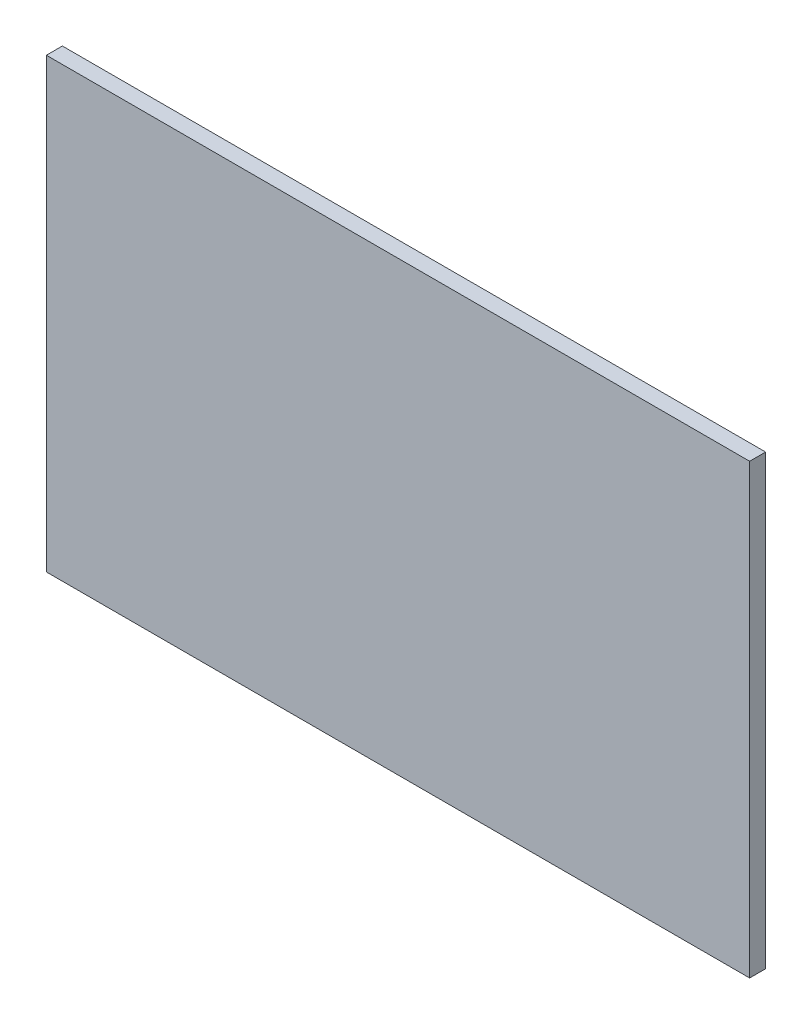
SolidWorks part; units mm, degrees
material "Glass"
ref_plane "Front Plane" through (0, 0, 0) normal (0, 0, 1) x (1, 0, 0)
ref_plane "Top Plane" through (0, 0, 0) normal (0, 1, 0) x (1, 0, 0)
ref_plane "Right Plane" through (0, 0, 0) normal (1, 0, 0) x (0, 0, -1)
sketch "Sketch1" plane through (0, 0, 0) normal (0, 0, 1) x (1, 0, 0)
  line L1 (-110, 70) -> (110, 70)
  line L2 (-110, 70) -> (-110, -70)
  line L3 (-110, -70) -> (110, -70)
  line L4 (110, 70) -> (110, -70)
  line L5 (-110, 70) -> (110, -70) construction
  line L6 (-110, -70) -> (110, 70) construction
  point P0 (0, 0)
  dimension "D1" = 220
  dimension "D2" = 140
extrude "Boss-Extrude1" add sketch "Sketch1" along normal blind 5
equation "\"width\"= 220mm"
equation "\"height\"= 140mm"
equation "\"D1@Sketch1\"=\"width\""
equation "\"D2@Sketch1\"=\"height\""
equation "\"sheetThickness\"= 5mm"
equation "\"D1@Boss-Extrude1\"=\"sheetThickness\""
